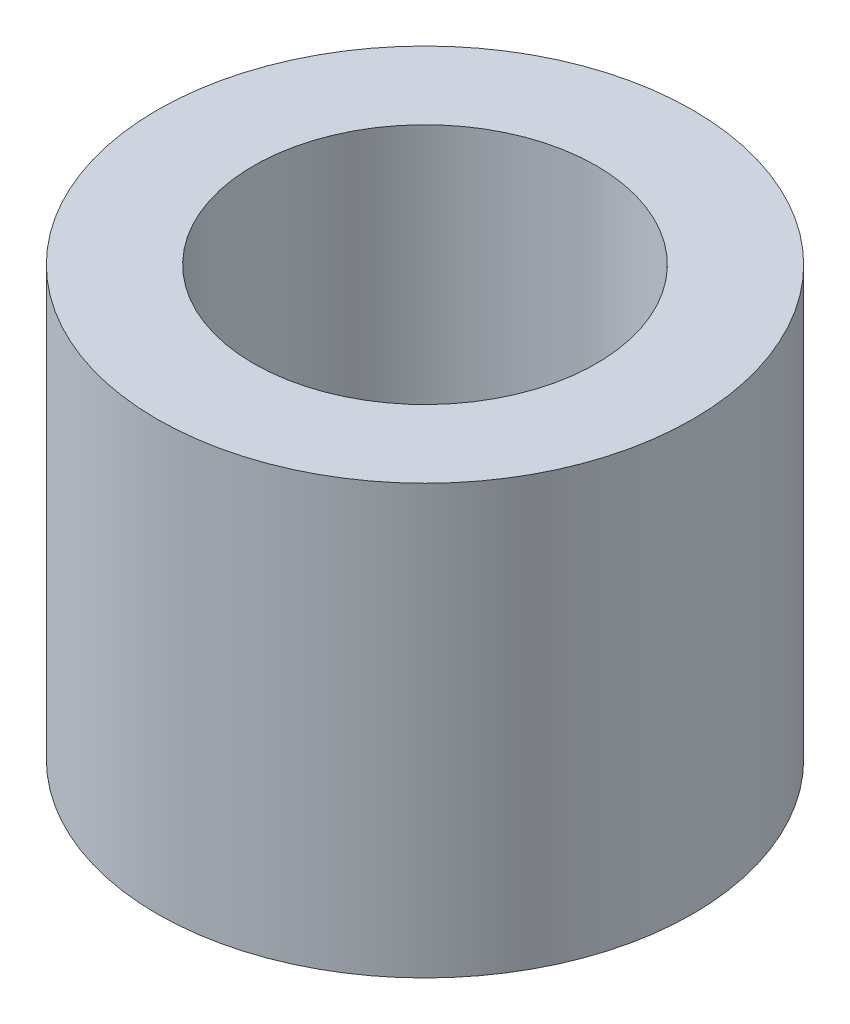
SolidWorks part; units mm, degrees
material "Alumina"
ref_plane "Front Plane" through (0, 0, 0) normal (0, 0, 1) x (1, 0, 0)
ref_plane "Top Plane" through (0, 0, 0) normal (0, 1, 0) x (1, 0, 0)
ref_plane "Right Plane" through (0, 0, 0) normal (1, 0, 0) x (0, 0, -1)
sketch "Sketch1" plane through (0, 0, 0) normal (0, 1, 0) x (1, 0, 0)
  circle A0 centre (0, 0) radius 3.175
  dimension "D1" = 6.35
extrude "Boss-Extrude1" add sketch "Sketch1" along normal blind 5.08
sketch "Sketch2" plane through (0, 5.08, 0) normal (0, 1, 0) x (1, 0, 0)
  circle A0 centre (0, 0) radius 2.032
  dimension "D1" = 4.064
extrude "Cut-Extrude1" cut sketch "Sketch2" against normal through all contours A0
